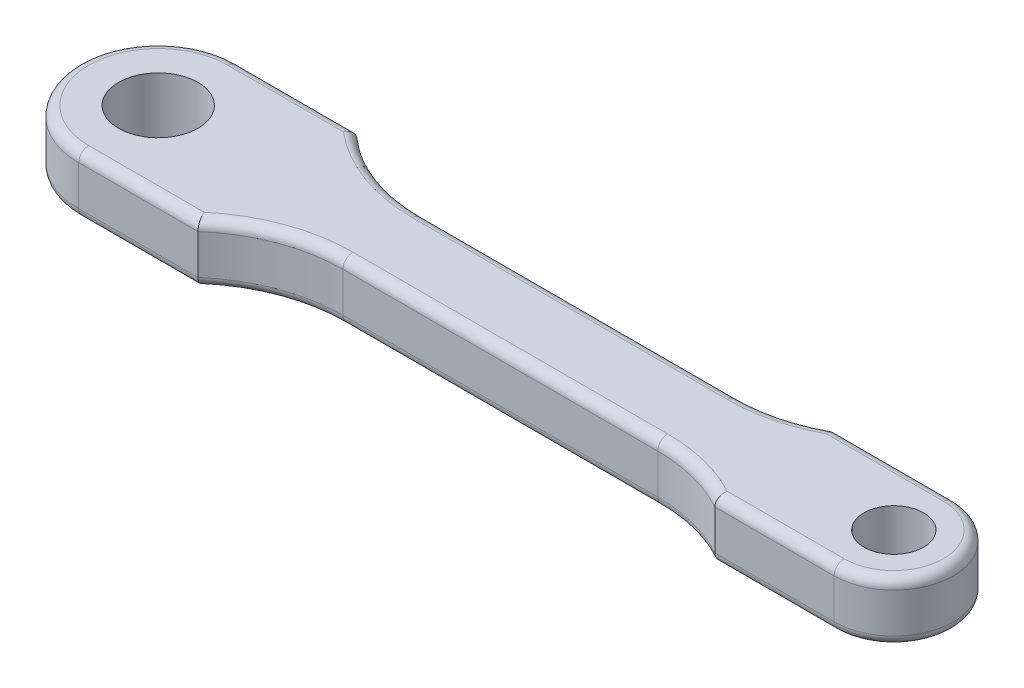
SolidWorks part; units mm, degrees
ref_plane "Ön Düzlem" through (0, 0, 0) normal (0, 0, 1) x (1, 0, 0)
ref_plane "Üst Düzlem" through (0, 0, 0) normal (0, 1, 0) x (1, 0, 0)
ref_plane "Sağ Düzlem" through (0, 0, 0) normal (1, 0, 0) x (0, 0, -1)
sketch "Sketch1" plane through (0, 0, 0) normal (0, 1, 0) x (1, 0, 0)
  line L0 (-18.5, 0) -> (18.5, 0) construction
  line L1 (-18.5, 4) -> (-12.5, 4)
  line L2 (-18.5, -4) -> (-12.5, -4)
  line L3 (18.5, 3) -> (12.5, 3)
  line L4 (18.5, -3) -> (12.5, -3)
  line L5 (-7.2085, 2) -> (8.627, 2)
  line L6 (-7.2085, -2) -> (8.627, -2)
  circle A0 centre (-18.5, 0) radius 4
  circle A1 centre (18.5, 0) radius 3
  arc A2 (12.5, 3) -> (8.627, 2) centre (8.627, 10) cw
  arc A3 (12.5, -3) -> (8.627, -2) centre (8.627, -10) ccw
  arc A4 (-12.5, 4) -> (-7.2085, 2) centre (-7.2085, 10) ccw
  arc A5 (-12.5, -4) -> (-7.2085, -2) centre (-7.2085, -10) cw
  circle A6 centre (-18.5, 0) radius 2
  circle A7 centre (18.5, 0) radius 1.5
  dimension "D1" = 37
  dimension "D3" = 8
  dimension "D4" = 6
  dimension "D2" = 4
  dimension "D5" = 6
  dimension "D6" = 6
extrude "Boss-Extrude1" add sketch "Sketch1" along normal mid plane 3
scale "Scale1" scale about centroid uniform scaling yes scale factor 1.5
fillet "Fillet1" radius 0.75 24 edges at (24.0912, -2.25, 4.5) (24.0912, 2.25, 4.5) (24.0912, -2.25, -4.5) (24.0912, 2.25, -4.5) (-22.4088, -2.25, -6) (-22.4088, 2.25, -6) (-22.4088, -2.25, 6) (-22.4088, 2.25, 6) (-14.2142, -2.25, -3.775) (-14.2142, 2.25, -3.775) (16.7817, -2.25, -3.381) (16.7817, 2.25, -3.381) (33.0912, -2.25, 0) (33.0912, 2.25, 0) (-14.2142, -2.25, 3.775) (-14.2142, 2.25, 3.775) (16.7817, -2.25, 3.381) (16.7817, 2.25, 3.381) (-32.9088, -2.25, 0) (-32.9088, 2.25, 0) (1.9051, -2.25, -3) (1.9051, 2.25, -3) (1.9051, -2.25, 3) (1.9051, 2.25, 3)
